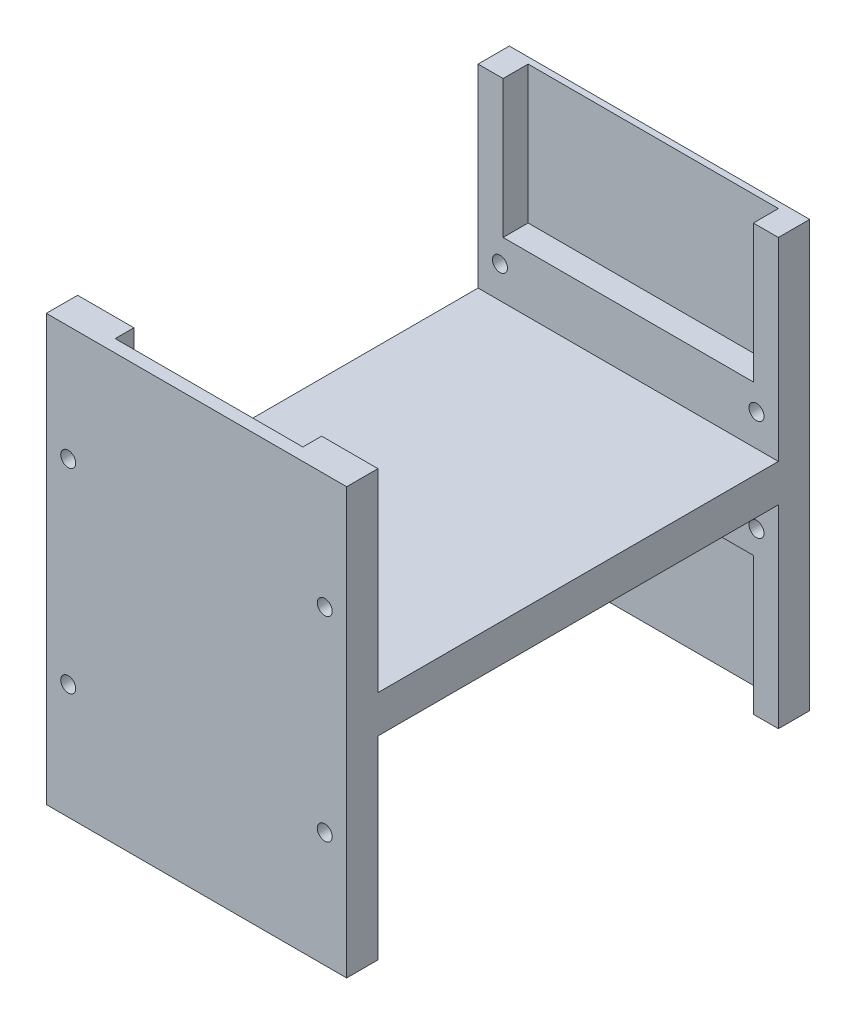
SolidWorks part; units mm, degrees
ref_plane "前视基准面" through (0, 0, 0) normal (0, 0, 1) x (1, 0, 0)
ref_plane "上视基准面" through (0, 0, 0) normal (0, 1, 0) x (1, 0, 0)
ref_plane "右视基准面" through (0, 0, 0) normal (1, 0, 0) x (0, 0, -1)
other "Configuration Table"
sketch "草图1" plane through (0, 0, 0) normal (0, 0, 1) x (1, 0, 0)
  line L1 (0, 0) -> (24, 0)
  line L2 (0, 0) -> (0, 17)
  line L3 (0, 17) -> (24, 17)
  line L4 (24, 0) -> (24, 17)
  dimension "D1" = 17
  dimension "D2" = 24
extrude "凸台-拉伸1" add sketch "草图1" along normal blind 37
sketch "草图2" plane through (0, 0, 0) normal (0, -1, 0) x (1, 0, 0)
  line L0 (0, 18.5) -> (-50000, 18.5) construction
  line L1 (0, 37) -> (0, 0) construction
  line L2 (24, 37) -> (24, 0) construction
  line L3 (0, 34.5) -> (24, 34.5)
  line L4 (0, 34.5) -> (0, 2.5)
  line L5 (0, 2.5) -> (24, 2.5)
  line L6 (24, 34.5) -> (24, 2.5)
  point P4 (0, 18.5)
  point P9 (0, 18.5)
  line M7 (24, 0) -> (24, 37)
  line M9 (0, 37) -> (0, 0)
  dimension "D1" = 32
extrude "切除-拉伸1" cut sketch "草图2" against normal offset from surface (15.5 mm away) 1.5 contours L0 L6 L3 M9 | L0 L4 L5 M7 up to face at (12, 17, 18.5)
sketch "草图3" plane through (0, 0, 37) normal (0, 0, 1) x (1, 0, 0)
  line L0 (12, 0) -> (12, -50000) construction
  line L1 (0, 0) -> (24, 0) construction
  line L3 (1.75, 9.2) -> (22.25, 9.2) construction
  line L4 (1.75, 9.2) -> (1.75, 0) construction
  line L5 (1.75, 0) -> (22.25, 0) construction
  line L6 (22.25, 9.2) -> (22.25, 0) construction
  circle A0 centre (1.75, 9.2) radius 0.6
  circle A1 centre (22.25, 9.2) radius 0.6
  point P4 (12, 0)
  point P9 (12, 9.2)
  dimension "D3" = 1.2
  dimension "D4" = 1.2
  dimension "D1" = 9.2
  dimension "D2" = 20.5
extrude "切除-拉伸2" cut sketch "草图3" against normal up to next
sketch "草图4" plane through (0, 0, 0) normal (0, 0, -1) x (-1, 0, 0)
  line L0 (-12, 0) -> (-12, -50000) construction
  line L1 (0, 0) -> (-24, 0) construction
  line L3 (-22.25, 12.95) -> (-1.75, 12.95) construction
  line L4 (-22.25, 12.95) -> (-22.25, 0) construction
  line L5 (-22.25, 0) -> (-1.75, 0) construction
  line L6 (-1.75, 12.95) -> (-1.75, 0) construction
  circle A0 centre (-22.25, 12.95) radius 0.6
  circle A1 centre (-1.75, 12.95) radius 0.6
  point P4 (-12, 0)
  point P9 (-12, 12.95)
  dimension "D3" = 1.2
  dimension "D4" = 1.2
  dimension "D1" = 20.5
  dimension "D2" = 12.95
extrude "切除-拉伸3" cut sketch "草图4" against normal up to next
sketch "草图5" plane through (0, 0, 0) normal (0, -1, 0) x (1, 0, 0)
  line L0 (12, 2.5) -> (12, -49997.5) construction
  line L1 (24, 2.5) -> (0, 2.5) construction
  line L2 (0, 2.5) -> (24, 2.5) construction
  line L3 (2, 2.5) -> (22, 2.5)
  line L4 (2, 2.5) -> (2, 0.5)
  line L5 (2, 0.5) -> (22, 0.5)
  line L6 (22, 2.5) -> (22, 0.5)
  point P4 (12, 2.5)
  point P11 (12, 0.5)
  dimension "D1" = 2
  dimension "D2" = 20
extrude "切除-拉伸4" cut sketch "草图5" against normal blind 11
sketch "草图6" plane through (0, 0, 0) normal (0, -1, 0) x (1, 0, 0)
  line L0 (12, 37) -> (12, -49963) construction
  line L1 (0, 37) -> (24, 37) construction
  line L2 (0, 34.5) -> (24, 34.5) construction
  line L3 (4.5, 36) -> (19.5, 36)
  line L4 (4.5, 36) -> (4.5, 34.5)
  line L5 (4.5, 34.5) -> (19.5, 34.5)
  line L6 (19.5, 36) -> (19.5, 34.5)
  point P4 (12, 37)
  point P9 (12, 36)
  dimension "D1" = 15
  dimension "D2" = 1.5
extrude "切除-拉伸5" cut sketch "草图6" against normal blind 15
ref_plane "基准面1" through (0, 17, 0) normal (0, 1, 0) x (1, 0, 0)
mirror "镜向1" about plane through (0, 17, 0) normal (0, 1, 0) of bodies 111
